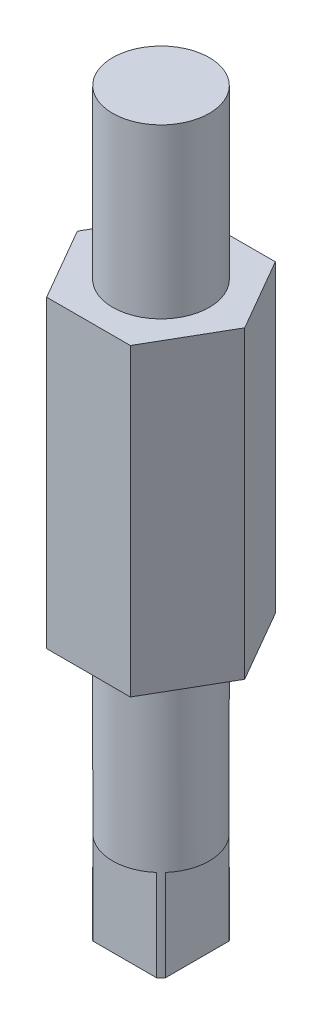
SolidWorks part; units mm, degrees
ref_plane "Front Plane" through (0, 0, 0) normal (0, 0, 1) x (1, 0, 0)
ref_plane "Top Plane" through (0, 0, 0) normal (0, 1, 0) x (1, 0, 0)
ref_plane "Right Plane" through (0, 0, 0) normal (1, 0, 0) x (0, 0, -1)
sketch "Sketch1" plane through (0, 0, 0) normal (0, 1, 0) x (1, 0, 0)
  line L1 (5.4993, 9.525) -> (-5.4993, 9.525)
  line L2 (-5.4993, 9.525) -> (-10.9985, 0)
  line L3 (-10.9985, 0) -> (-5.4993, -9.525)
  line L4 (-5.4993, -9.525) -> (5.4993, -9.525)
  line L5 (5.4993, -9.525) -> (10.9985, 0)
  line L6 (10.9985, 0) -> (5.4993, 9.525)
  circle A0 centre (0, 0) radius 9.525 construction
  dimension "D1" = 19.05
extrude "Boss-Extrude1" add sketch "Sketch1" along normal blind 97.0775
sketch "Sketch2" plane through (0, 97.0775, 0) normal (0, 1, 0) x (1, 0, 0)
  line L6 (10.9985, 0) -> (5.4993, 9.525)
  line L7 (5.4993, 9.525) -> (-5.4993, 9.525)
  line L8 (-5.4993, 9.525) -> (-10.9985, 0)
  line L9 (-10.9985, 0) -> (-5.4993, -9.525)
  line L10 (-5.4993, -9.525) -> (5.4993, -9.525)
  line L11 (5.4993, -9.525) -> (10.9985, 0)
  line L12 (10.9985, 0) -> (5.4993, 9.525)
  line L13 (5.4993, 9.525) -> (-5.4993, 9.525)
  line L14 (-5.4993, 9.525) -> (-10.9985, 0)
  line L15 (-10.9985, 0) -> (-5.4993, -9.525)
  line L16 (-5.4993, -9.525) -> (5.4993, -9.525)
  line L17 (5.4993, -9.525) -> (10.9985, 0)
  circle A0 centre (0, 0) radius 6.35
  dimension "D1" = 12.7
  dimension "D2" = 0
extrude "Cut-Extrude1" cut sketch "Sketch2" against normal blind 22.08
sketch "Sketch3" plane through (0, 0, 0) normal (0, -1, 0) x (1, 0, 0)
  line L6 (5.4993, -9.525) -> (10.9985, 0)
  line L7 (10.9985, 0) -> (5.4993, 9.525)
  line L8 (5.4993, 9.525) -> (-5.4993, 9.525)
  line L9 (-5.4993, 9.525) -> (-10.9985, 0)
  line L10 (-10.9985, 0) -> (-5.4993, -9.525)
  line L11 (-5.4993, -9.525) -> (5.4993, -9.525)
  line L12 (5.4993, -9.525) -> (10.9985, 0)
  line L13 (10.9985, 0) -> (5.4993, 9.525)
  line L14 (5.4993, 9.525) -> (-5.4993, 9.525)
  line L15 (-5.4993, 9.525) -> (-10.9985, 0)
  line L16 (-10.9985, 0) -> (-5.4993, -9.525)
  line L17 (-5.4993, -9.525) -> (5.4993, -9.525)
  circle A0 centre (0, 0) radius 6.35
  dimension "D1" = 12.7
  dimension "D2" = 0
extrude "Cut-Extrude2" cut sketch "Sketch3" against normal blind 35
sketch "Sketch4" plane through (0, 0, 0) normal (0, -1, 0) x (1, 0, 0)
  line L1 (-4.7625, -4.7625) -> (4.7625, -4.7625)
  line L2 (-4.7625, -4.7625) -> (-4.7625, 4.7625)
  line L3 (-4.7625, 4.7625) -> (4.7625, 4.7625)
  line L4 (4.7625, -4.7625) -> (4.7625, 4.7625)
  line L5 (-4.7625, -4.7625) -> (4.7625, 4.7625) construction
  line L6 (-4.7625, 4.7625) -> (4.7625, -4.7625) construction
  line L12 (-5.4993, -9.525) -> (5.4993, -9.525)
  line L13 (5.4993, -9.525) -> (10.9985, 0)
  line L14 (10.9985, 0) -> (5.4993, 9.525)
  line L15 (5.4993, 9.525) -> (-5.4993, 9.525)
  line L16 (-5.4993, 9.525) -> (-10.9985, 0)
  line L17 (-10.9985, 0) -> (-5.4993, -9.525)
  line L18 (-5.4993, -9.525) -> (5.4993, -9.525)
  line L19 (5.4993, -9.525) -> (10.9985, 0)
  line L20 (10.9985, 0) -> (5.4993, 9.525)
  line L21 (5.4993, 9.525) -> (-5.4993, 9.525)
  line L22 (-5.4993, 9.525) -> (-10.9985, 0)
  line L23 (-10.9985, 0) -> (-5.4993, -9.525)
  point P0 (0, 0)
  dimension "D1" = 9.525
  dimension "D2" = 0
extrude "Cut-Extrude3" cut sketch "Sketch4" against normal blind 12
